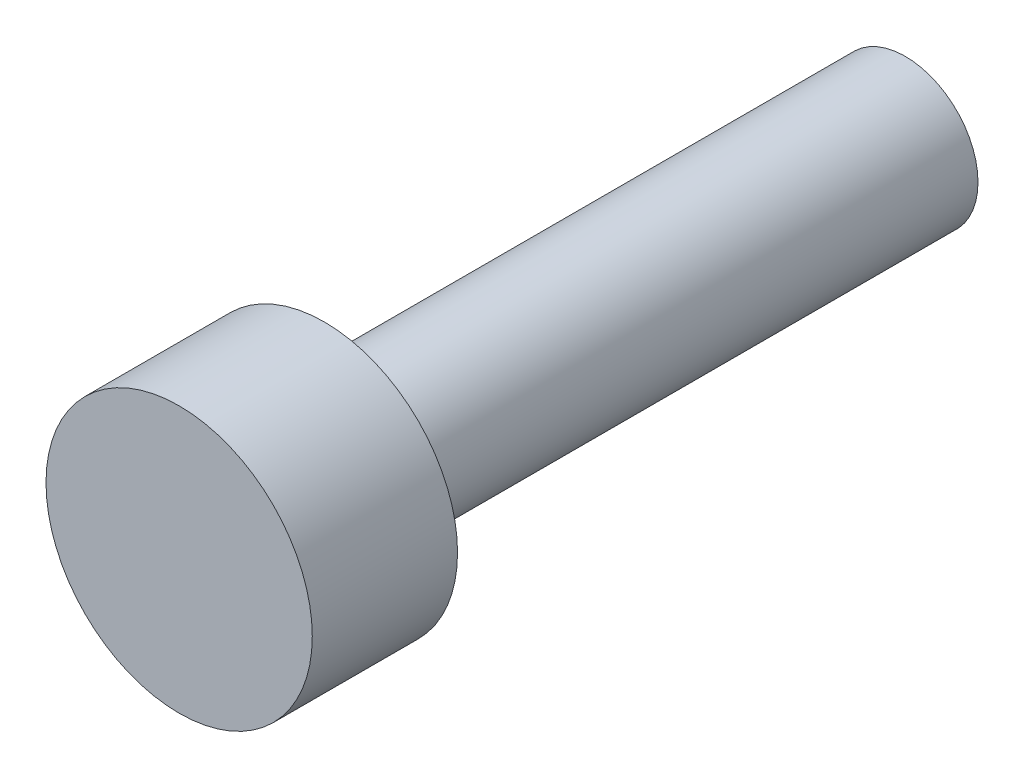
SolidWorks part; units mm, degrees
ref_plane "前视基准面" through (0, 0, 0) normal (0, 0, 1) x (1, 0, 0)
ref_plane "上视基准面" through (0, 0, 0) normal (0, 1, 0) x (1, 0, 0)
ref_plane "右视基准面" through (0, 0, 0) normal (1, 0, 0) x (0, 0, -1)
other "Configuration Table"
sketch "Sketch_Nominal_shank" plane through (0, 0, 0) normal (0, 0, 1) x (1, 0, 0)
  circle A0 centre (0, 0) radius 1.5
  dimension "D1" = 3
extrude "Nominal_shank" add sketch "Sketch_Nominal_shank" along normal blind 12 from offset 12
sketch "Sketch_Head" plane through (0, 0, 0) normal (0, 0, 1) x (1, 0, 0)
  circle A0 centre (0, 0) radius 2.75
  dimension "D1" = 5.5
extrude "Head" add sketch "Sketch_Head" along normal blind 3 from offset 0
